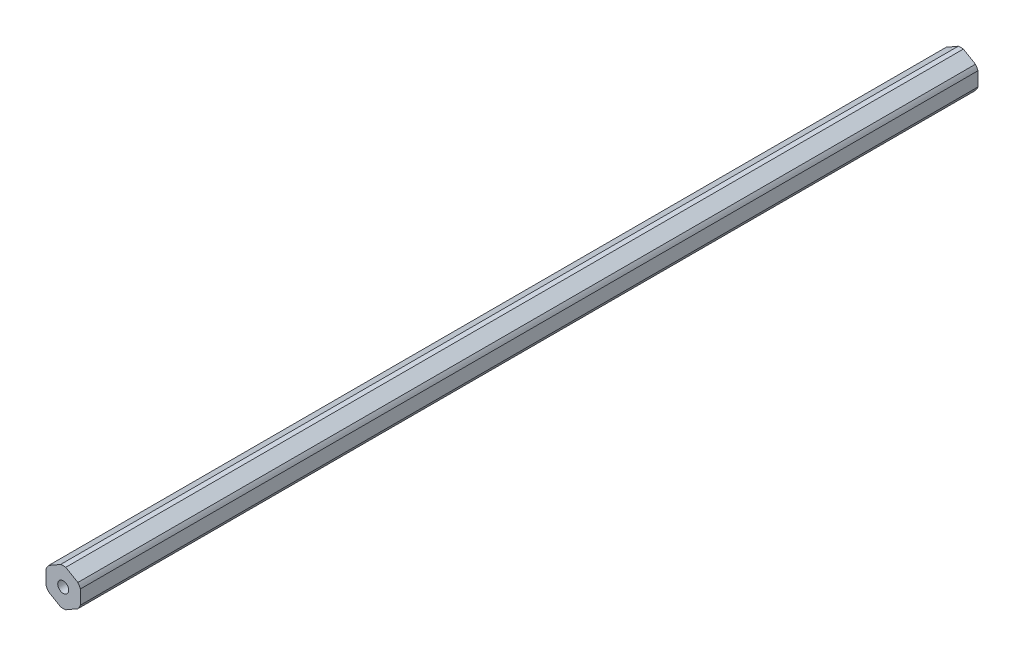
SolidWorks part; units mm, degrees
ref_plane "Front Plane" through (0, 0, 0) normal (0, 0, 1) x (1, 0, 0)
ref_plane "Top Plane" through (0, 0, 0) normal (0, 1, 0) x (1, 0, 0)
ref_plane "Right Plane" through (0, 0, 0) normal (1, 0, 0) x (0, 0, -1)
sketch "Sketch1" plane through (0, 0, 0) normal (0, 0, 1) x (1, 0, 0)
  line L1 (0, 7.3323) -> (-6.35, 3.6662)
  line L2 (-6.35, 3.6662) -> (-6.35, -3.6662)
  line L3 (-6.35, -3.6662) -> (0, -7.3323)
  line L4 (0, -7.3323) -> (6.35, -3.6662)
  line L5 (6.35, -3.6662) -> (6.35, 3.6662)
  line L6 (6.35, 3.6662) -> (0, 7.3323)
  circle A0 centre (0, 0) radius 6.35 construction
  circle A1 centre (0, 0) radius 6.858
  dimension "D1" = 12.7
  dimension "D2" = 13.716
extrude "Boss-Extrude1" add sketch "Sketch1" along normal mid plane 331.3278 contours L5 A1 L6 L1 L2 L3 L4
hole_wizard "#10-32 Tapped Hole1" positions "3DSketch1" profile "Sketch2" tap size "#10-32" standard "ANSI Inch"
sketch3d "3DSketch1"
  line L0 (0, 0, 165.6639) -> (0, 0, -165.6639) construction
  line L1 (0, 0, 165.6639) -> (0, 0, -165.6639) construction
  point P0 (0, 0, 165.6639)
  point P4 (0, 0, -165.6639)
sketch "Sketch2" plane through (0, 0, 165.6639) normal (1, 0, 0) x (0, -1, 0)
  line L0 (0, 0) -> (0, 17.5608)
  line L1 (0, 17.5608) -> (2.0193, 16.3474)
  line L2 (2.0193, 16.3474) -> (2.0193, 0)
  line L5 (2.0193, 0) -> (0, 0)
  line L10 (0, 17.5608) -> (-2.0193, 16.3474) construction
  line L11 (0, -6.35) -> (0, 107.95) construction
  dimension "Tap Drill Dia." = 4.0386
  dimension "Tap Drill Depth" = 16.3474
  dimension "Drill Angle" = 118
cosmetic thread "Hole Thread1" parameters "D1"=13.97, "D2"=4.826
cosmetic thread "Hole Thread2" parameters "D1"=13.97, "D2"=4.826
sketch "Sketch3" plane through (0, 0, 0) normal (1, 0, 0) x (0, 0, -1)
  line L0 (-175.1574, 0) -> (-171.1173, 0) construction
  line L1 (165.6639, 6.858) -> (-165.6639, 6.858) construction
  line L2 (-164.0764, 6.858) -> (-163.1874, 6.858)
  line L3 (-164.0764, 6.858) -> (-164.0764, 5.8547)
  line L4 (-164.0764, 5.8547) -> (-163.1874, 5.8547)
  line L5 (-163.1874, 6.858) -> (-163.1874, 5.8547)
  dimension "D1" = 0.889
  dimension "D2" = 5.8547
  dimension "D3" = 1.5875
